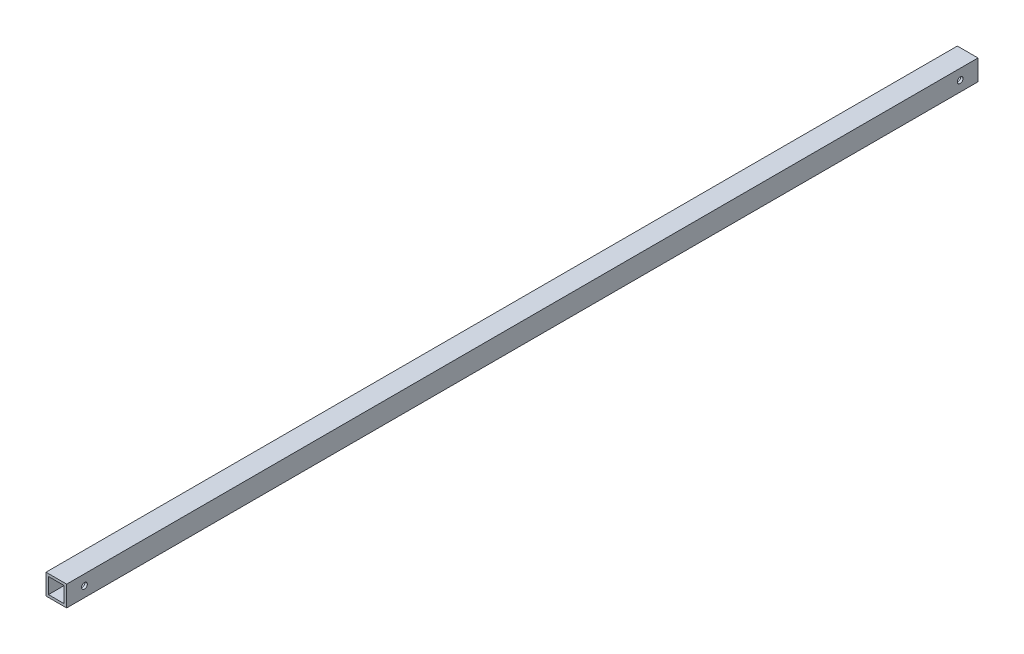
SolidWorks part; units mm, degrees
ref_plane "前视基准面" through (0, 0, 0) normal (0, 0, 1) x (1, 0, 0)
ref_plane "上视基准面" through (0, 0, 0) normal (0, 1, 0) x (1, 0, 0)
ref_plane "右视基准面" through (0, 0, 0) normal (1, 0, 0) x (0, 0, -1)
sketch "草图1" plane through (0, 0, 0) normal (0, 0, 1) x (1, 0, 0)
  line L1 (0, 0) -> (25, 0)
  line L2 (0, 0) -> (0, -25)
  line L3 (0, -25) -> (25, -25)
  line L4 (25, 0) -> (25, -25)
  line L5 (3, -3) -> (22, -3)
  line L6 (3, -3) -> (3, -22)
  line L7 (3, -22) -> (22, -22)
  line L8 (22, -3) -> (22, -22)
  dimension "D1" = 3
  dimension "D2" = 3
  dimension "D3" = 3
  dimension "D4" = 3
  dimension "D5" = 25
  dimension "D6" = 25
extrude "拉伸1" add sketch "草图1" along normal blind 1102.75
hole_wizard "Ø7.0 (7) 直径孔1" positions "草图5" profile "草图4" hole size "Ø7.0" standard "GB"
sketch "草图5" plane through (0, 0, 0) normal (-1, 0, 0) x (0, 0, 1)
  line L0 (1102.75, 0) -> (0, 0) construction
  line L1 (1102.75, 0) -> (1102.75, -25) construction
  point P0 (1081.25, -12.5)
  dimension "D1" = 12.5
  dimension "D2" = 21.5
sketch "草图4" plane through (0, -12.5, 1081.25) normal (0, 1, 0) x (0, 0, 1)
  line L0 (0, 0) -> (0, 32.103)
  line L1 (0, 32.103) -> (3.5, 30)
  line L2 (3.5, 30) -> (3.5, 0)
  line L5 (3.5, 0) -> (0, 0)
  line L10 (0, 32.103) -> (-3.5, 30) construction
  line L11 (0, -6.35) -> (0, 107.95) construction
  dimension "孔直径" = 7
  dimension "孔深度" = 30
  dimension "导头角度" = 118
pattern_linear "阵列(线性)1" count 2 spacing 1059.69 along (0, 0, -1) of "Ø7.0 (7) 直径孔1"
